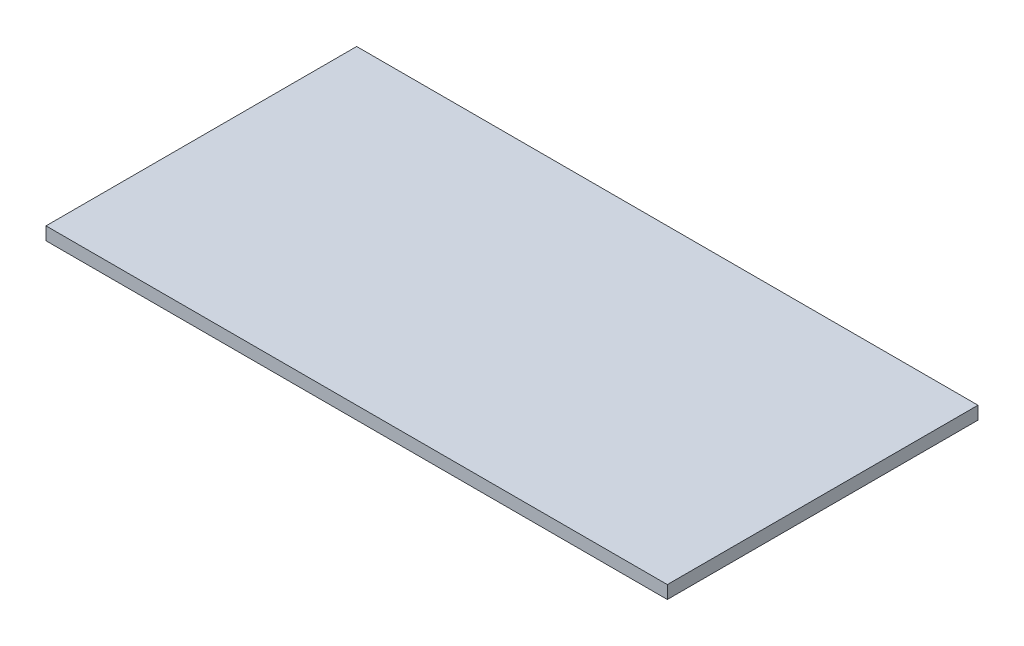
SolidWorks part; units mm, degrees
ref_plane "Front Plane" through (0, 0, 0) normal (0, 0, 1) x (1, 0, 0)
ref_plane "Top Plane" through (0, 0, 0) normal (0, 1, 0) x (1, 0, 0)
ref_plane "Right Plane" through (0, 0, 0) normal (1, 0, 0) x (0, 0, -1)
sketch "Sketch1" plane through (0, 0, 0) normal (0, 1, 0) x (1, 0, 0)
  line L1 (-304.8, -152.4) -> (304.8, -152.4)
  line L2 (-304.8, -152.4) -> (-304.8, 152.4)
  line L3 (-304.8, 152.4) -> (304.8, 152.4)
  line L4 (304.8, -152.4) -> (304.8, 152.4)
  line L5 (-304.8, -152.4) -> (304.8, 152.4) construction
  line L6 (-304.8, 152.4) -> (304.8, -152.4) construction
  point P0 (0, 0)
  dimension "D1" = 609.6
  dimension "D2" = 304.8
extrude "Boss-Extrude1" add sketch "Sketch1" along normal blind 12.7
